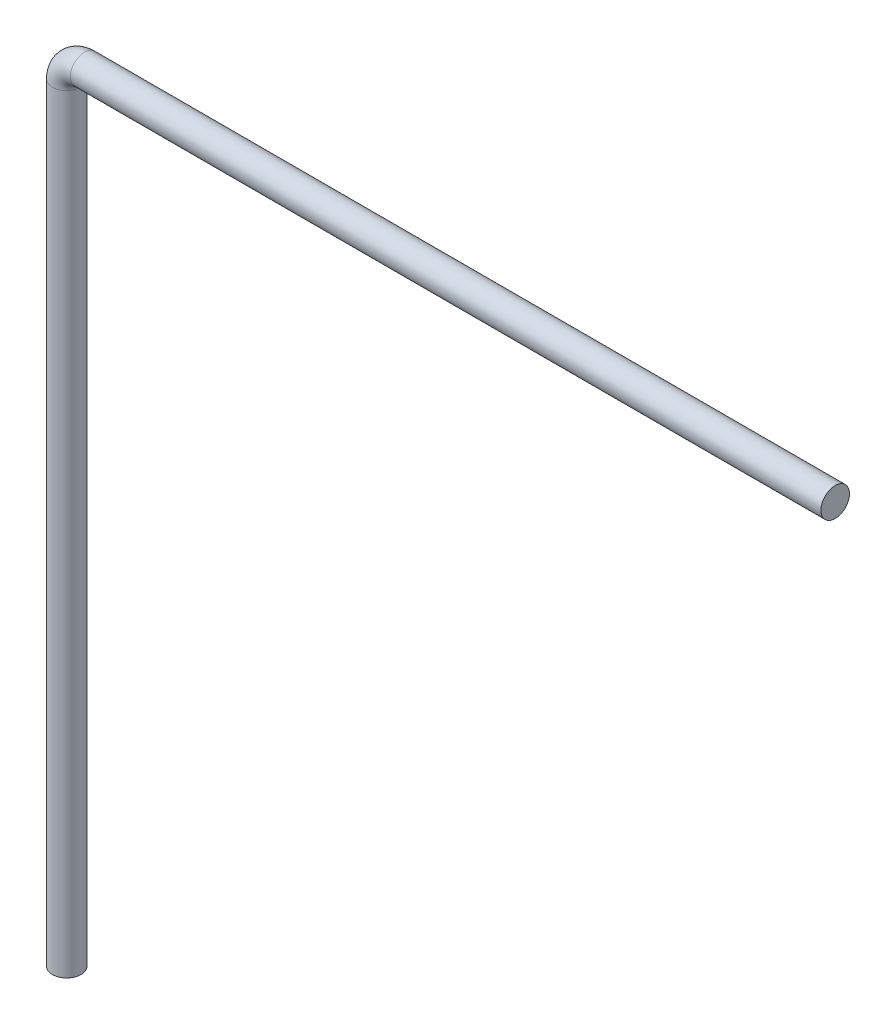
SolidWorks part; units mm, degrees
material "Медь"
ref_plane "Спереди" through (0, 0, 0) normal (0, 0, 1) x (1, 0, 0)
ref_plane "Сверху" through (0, 0, 0) normal (0, 1, 0) x (1, 0, 0)
ref_plane "Справа" through (0, 0, 0) normal (1, 0, 0) x (0, 0, -1)
sketch "Эскиз1" plane through (0, 0, 0) normal (0, 0, 1) x (1, 0, 0)
  line L0 (0, 0) -> (0, 21.5)
  line L1 (0.5, 22) -> (21.5, 22)
  arc A0 (0, 21.5) -> (0.5, 22) centre (0.5, 21.5) cw
  point P6 (0, 22)
  dimension "D3" = 0.5
  dimension "D1" = 21.5
  dimension "D2" = 21.5
sketch "Эскиз2" plane through (0, 0, 0) normal (0, 1, 0) x (1, 0, 0)
  circle A0 centre (0, 0) radius 0.4
  dimension "D1" = 0.8
sweep "По траектории1" add profiles "Эскиз2" path "Эскиз1"
